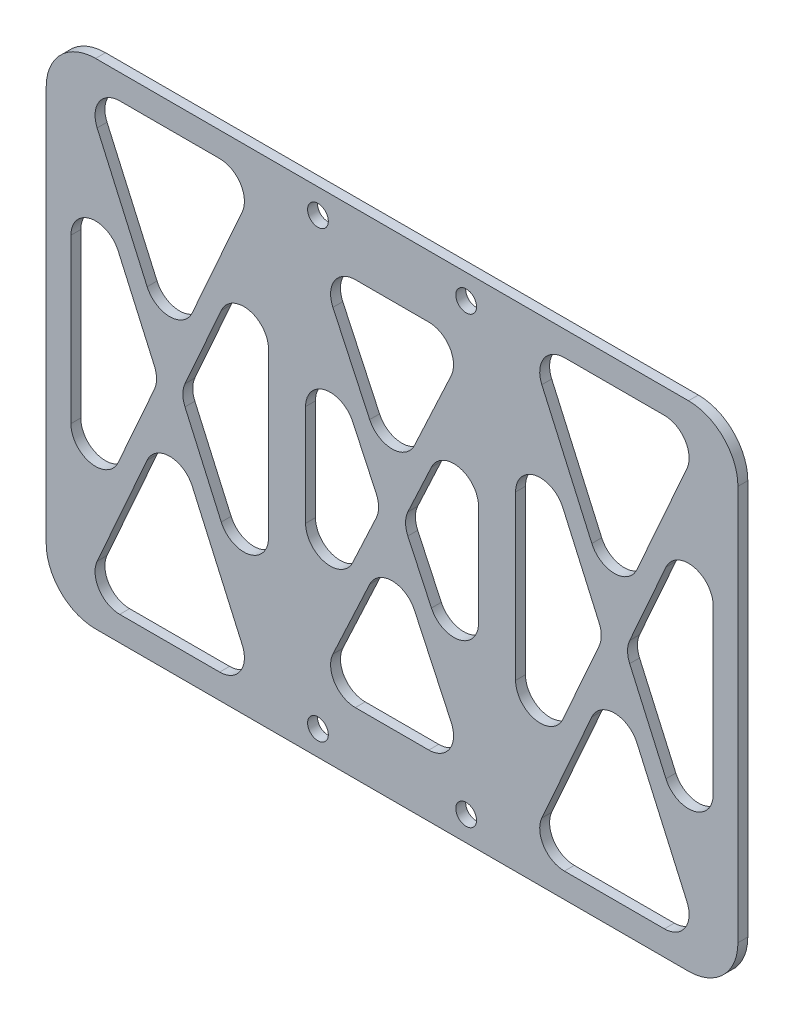
SolidWorks part; units mm, degrees
ref_plane "前视基准面" through (0, 0, 0) normal (0, 0, 1) x (1, 0, 0)
ref_plane "上视基准面" through (0, 0, 0) normal (0, 1, 0) x (1, 0, 0)
ref_plane "右视基准面" through (0, 0, 0) normal (1, 0, 0) x (0, 0, -1)
sketch "草图1" plane through (0, 0, 0) normal (0, 0, 1) x (1, 0, 0)
  line L1 (70, 50) -> (-70, 50)
  line L2 (70, 50) -> (70, -50)
  line L3 (70, -50) -> (-70, -50)
  line L4 (-70, 50) -> (-70, -50)
  line L5 (70, 50) -> (-70, -50) construction
  line L6 (70, -50) -> (-70, 50) construction
  point P0 (0, 0)
  dimension "D1" = 140
  dimension "D2" = 100
extrude "凸台-拉伸1" add sketch "草图1" along normal blind 2
sketch "草图3" plane through (0, 0, 0) normal (0, 0, -1) x (-1, 0, 0)
  line L0 (0, 0) -> (0, -34.4681) construction
  line L1 (0, 0) -> (-21.8502, 0) construction
  circle A0 centre (-15, -45) radius 2.1
  circle A1 centre (15, -45) radius 2.1
  circle A3 centre (15, 45) radius 2.1
  circle A4 centre (-15, 45) radius 2.1
  dimension "D1" = 4.2
  dimension "D2" = 45
  dimension "D3" = 15
extrude "切除-拉伸2" cut sketch "草图3" against normal blind 10
sketch "草图4" plane through (0, 0, 0) normal (0, 0, -1) x (-1, 0, 0)
  line L0 (-17.5, 32.7706) -> (-2.2071, 0)
  line L1 (-15.2929, -37.5) -> (15.2929, -37.5)
  line L2 (-17.5, -32.7706) -> (-17.5, 32.7706)
  line L3 (-15.2929, 37.5) -> (15.2929, 37.5)
  line L4 (17.5, -32.7706) -> (17.5, 32.7706)
  line L5 (-17.5, -37.5) -> (17.5, 37.5) construction
  line L6 (-17.5, 37.5) -> (17.5, -37.5) construction
  line L7 (-15.2929, -37.5) -> (0, -4.7294)
  line L8 (-15.2929, 37.5) -> (0, 4.7294)
  line L9 (-17.5, -32.7706) -> (-2.2071, 0)
  line L10 (0, -4.7294) -> (15.2929, -37.5)
  line L11 (-19.3124, 36.6542) -> (15.6876, -38.3458) construction
  line L12 (-15.6876, 38.3458) -> (19.3124, -36.6542) construction
  line L13 (-19.3124, -36.6542) -> (15.6876, 38.3458) construction
  line L14 (-15.6876, -38.3458) -> (19.3124, 36.6542) construction
  line L15 (0, 4.7294) -> (15.2929, 37.5)
  line L16 (2.2071, 0) -> (17.5, -32.7706)
  line L17 (2.2071, 0) -> (17.5, 32.7706)
  line L18 (-62.8114, -45) -> (-45, -4.9244)
  line L19 (-62.8114, -45) -> (-27.1886, -45)
  line L20 (-65, -40.0756) -> (-65, 40.0756)
  line L21 (-62.8114, 45) -> (-27.1886, 45)
  line L22 (-25, -40.0756) -> (-25, 40.0756)
  line L23 (-65, -45) -> (-25, 45) construction
  line L24 (-65, 45) -> (-25, -45) construction
  line L25 (-65, 40.0756) -> (-47.1886, 0)
  line L26 (-65, -40.0756) -> (-47.1886, 0)
  line L27 (-62.8114, 45) -> (-45, 4.9244)
  line L28 (-42.8114, 0) -> (-25, -40.0756)
  line L29 (-66.8276, 44.1877) -> (-26.8276, -45.8123) construction
  line L30 (-63.1724, 45.8123) -> (-23.1724, -44.1877) construction
  line L31 (-66.8276, -44.1877) -> (-26.8276, 45.8123) construction
  line L32 (-63.1724, -45.8123) -> (-23.1724, 44.1877) construction
  line L33 (-45, 4.9244) -> (-27.1886, 45)
  line L34 (-45, -4.9244) -> (-27.1886, -45)
  line L35 (-42.8114, 0) -> (-25, 40.0756)
  line L36 (0, 41.9765) -> (0, -26.1642) construction
  line L37 (65, 45) -> (25, -45) construction
  line L38 (65, -45) -> (25, 45) construction
  line L39 (42.8114, 0) -> (25, 40.0756)
  line L40 (45, -4.9244) -> (27.1886, -45)
  line L41 (45, 4.9244) -> (27.1886, 45)
  line L42 (42.8114, 0) -> (25, -40.0756)
  line L43 (62.8114, 45) -> (45, 4.9244)
  line L44 (65, -40.0756) -> (47.1886, 0)
  line L45 (65, 40.0756) -> (47.1886, 0)
  line L46 (25, -40.0756) -> (25, 40.0756)
  line L47 (62.8114, 45) -> (27.1886, 45)
  line L48 (65, -40.0756) -> (65, 40.0756)
  line L49 (62.8114, -45) -> (27.1886, -45)
  line L50 (62.8114, -45) -> (45, -4.9244)
  point P0 (0, 0)
  point P23 (-45, 0)
  point P69 (45, 0)
  dimension "D1" = 35
  dimension "D2" = 75
  dimension "D5" = 45
  dimension "D6" = 40
  dimension "D9" = 90
  dimension "D3" = 2
  dimension "D4" = 2
  dimension "D7" = 2
  dimension "D8" = 2
extrude "切除-拉伸3" cut sketch "草图4" against normal blind 10
fillet "圆角1" radius 5 36 edges at (2.2071, 0, 1) (17.5, -32.7706, 1) (17.5, 32.7706, 1) (65, -40.0756, 1) (65, 40.0756, 1) (47.1886, 0, 1) (27.1886, 45, 1) (45, 4.9244, 1) (62.8114, 45, 1) (-15.2929, -37.5, 1) (15.2929, -37.5, 1) (0, -4.7294, 1) (-15.2929, 37.5, 1) (0, 4.7294, 1) (-17.5, -32.7706, 1) (-2.2071, 0, 1) (-17.5, 32.7706, 1) (-27.1886, -45, 1) (-45, -4.9244, 1) (-62.8114, -45, 1) (-47.1886, 0, 1) (-65, 40.0756, 1) (-65, -40.0756, 1) (-27.1886, 45, 1) (-62.8114, 45, 1) (-45, 4.9244, 1) (25, -40.0756, 1) (42.8114, 0, 1) (25, 40.0756, 1) (45, -4.9244, 1) (27.1886, -45, 1) (62.8114, -45, 1) (-25, 40.0756, 1) (-42.8114, 0, 1) (-25, -40.0756, 1) (15.2929, 37.5, 1)
fillet "圆角2" radius 10 4 edges at (70, 50, 1) (70, -50, 1) (-70, -50, 1) (-70, 50, 1)
